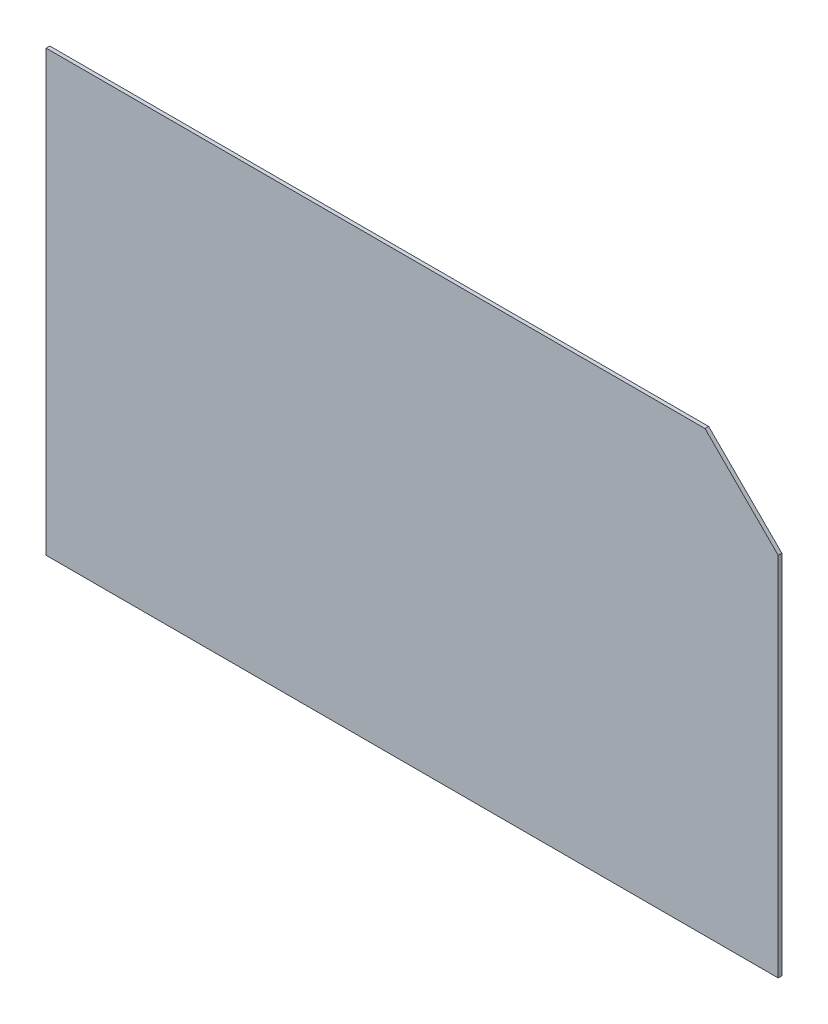
SolidWorks part; units mm, degrees
ref_plane "Front Plane" through (0, 0, 0) normal (0, 0, 1) x (1, 0, 0)
ref_plane "Top Plane" through (0, 0, 0) normal (0, 1, 0) x (1, 0, 0)
ref_plane "Right Plane" through (0, 0, 0) normal (1, 0, 0) x (0, 0, -1)
sketch "Sketch2" plane through (0, 0, 0) normal (0, 0, 1) x (1, 0, 0)
  line L1 (-2500, 1500) -> (2500, 1500)
  line L2 (-2500, 1500) -> (-2500, -1500)
  line L3 (-2500, -1500) -> (2500, -1500)
  line L4 (2500, 1500) -> (2500, -1500)
  dimension "wall_length" = 5000
  dimension "wall_height" = 3000
  dimension "D1" = 2500
  dimension "D2" = 1500
extrude "Boss-Extrude1" add sketch "Sketch2" against normal blind 25
sketch "Sketch3" plane through (0, 0, 0) normal (0, 0, 1) x (1, 0, 0)
  line L5 (2500, 1000) -> (2500, 1500)
  line L6 (2500, -1500) -> (2500, 1500) construction
  line L7 (2500, 1500) -> (2000, 1500)
  line L8 (2500, 1500) -> (-2500, 1500) construction
  line L9 (2000, 1500) -> (2500, 1000)
  dimension "D1" = 500
  dimension "D2" = 45
extrude "Cut-Extrude1" cut sketch "Sketch3" against normal blind 932
equation "\"D1@Sketch2\"=\"wall_length@Sketch2\"/2"
equation "\"D2@Sketch2\"=\"wall_height@Sketch2\"/2"
